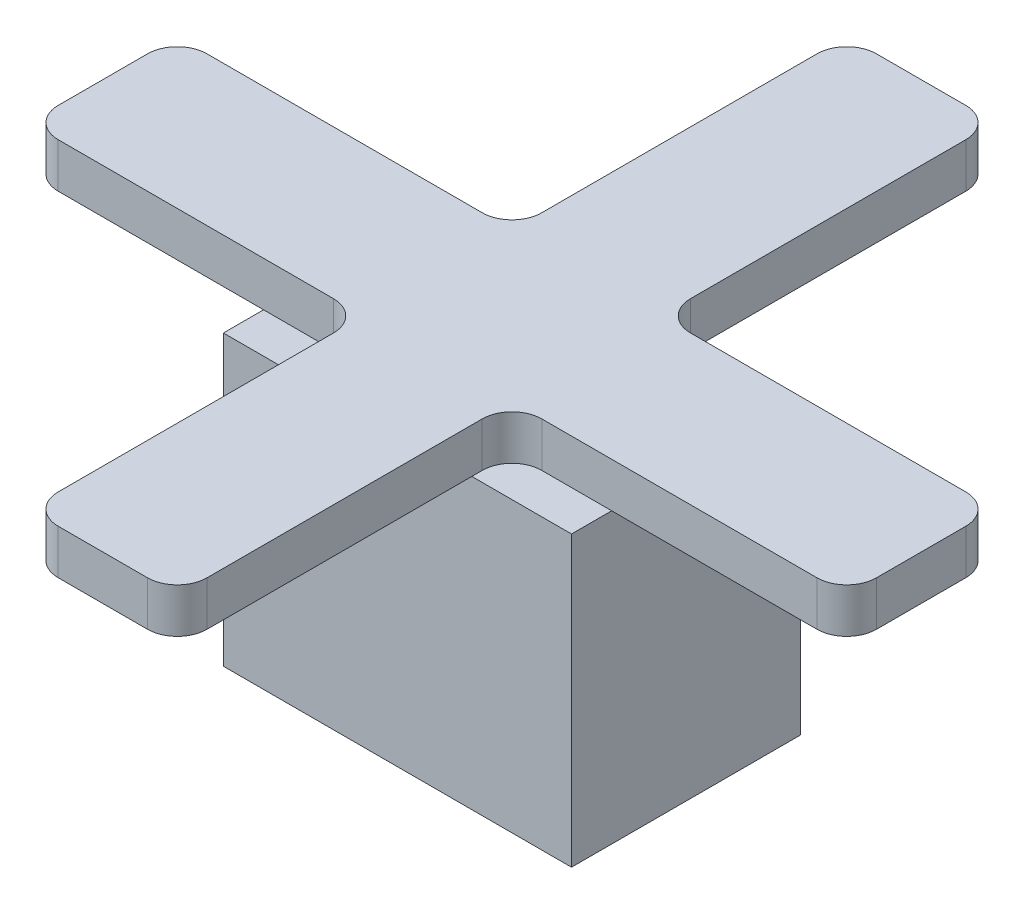
SolidWorks part; units mm, degrees
ref_plane "前视基准面" through (0, 0, 0) normal (0, 0, 1) x (1, 0, 0)
ref_plane "上视基准面" through (0, 0, 0) normal (0, 1, 0) x (1, 0, 0)
ref_plane "右视基准面" through (0, 0, 0) normal (1, 0, 0) x (0, 0, -1)
sketch "草图1" plane through (0, 0, 0) normal (0, 1, 0) x (1, 0, 0)
  line L0 (7, 5) -> (25.5, 5)
  line L1 (-25.5, 5) -> (-7, 5)
  line L2 (-27.5, 3) -> (-27.5, -3)
  line L3 (-25.5, -5) -> (-7, -5)
  line L4 (27.5, 3) -> (27.5, -3)
  line L7 (-3, 27.5) -> (3, 27.5)
  line L8 (-5, 25.5) -> (-5, 7)
  line L9 (-3, -27.5) -> (3, -27.5)
  line L10 (5, 25.5) -> (5, 7)
  line L16 (7, -5) -> (25.5, -5)
  line L17 (-5, -7) -> (-5, -25.5)
  line L18 (5, -7) -> (5, -25.5)
  arc A0 (3, -27.5) -> (5, -25.5) centre (3, -25.5) ccw
  arc A1 (-5, -25.5) -> (-3, -27.5) centre (-3, -25.5) ccw
  arc A2 (3, 27.5) -> (5, 25.5) centre (3, 25.5) cw
  arc A3 (-3, 27.5) -> (-5, 25.5) centre (-3, 25.5) ccw
  arc A4 (25.5, 5) -> (27.5, 3) centre (25.5, 3) cw
  arc A5 (-25.5, 5) -> (-27.5, 3) centre (-25.5, 3) ccw
  arc A6 (-27.5, -3) -> (-25.5, -5) centre (-25.5, -3) ccw
  arc A7 (-7, -5) -> (-5, -7) centre (-7, -7) cw
  arc A8 (5, -7) -> (7, -5) centre (7, -7) cw
  arc A9 (5, 7) -> (7, 5) centre (7, 7) ccw
  arc A10 (-5, 7) -> (-7, 5) centre (-7, 7) cw
  arc A11 (25.5, -5) -> (27.5, -3) centre (25.5, -3) ccw
  point P0 (0, 0)
  point P6 (0, 0)
  point P11 (0, 27.5)
  point P20 (5, 27.5)
  point P25 (-5, 27.5)
  point P28 (27.5, 5)
  point P31 (-27.5, 5)
  point P36 (-5, -5)
  point P45 (27.5, -5)
  dimension "D5" = 2
  dimension "D6" = 2
  dimension "D1" = 55
  dimension "D2" = 10
  dimension "D3" = 55
  dimension "D4" = 10
extrude "凸台-拉伸1" add sketch "草图1" along normal blind 3
sketch "草图2" plane through (0, 0, 0) normal (0, -1, 0) x (1, 0, 0)
  line L1 (-10.2, 6.2) -> (10.2, 6.2)
  line L2 (-10.2, 6.2) -> (-10.2, -6.2)
  line L3 (-10.2, -6.2) -> (10.2, -6.2)
  line L4 (10.2, 6.2) -> (10.2, -6.2)
  line L5 (-10.2, 6.2) -> (10.2, -6.2) construction
  line L6 (-10.2, -6.2) -> (10.2, 6.2) construction
  line L7 (-11.7, 7.7) -> (11.7, 7.7)
  line L8 (-11.7, 7.7) -> (-11.7, -7.7)
  line L9 (-11.7, -7.7) -> (11.7, -7.7)
  line L10 (11.7, 7.7) -> (11.7, -7.7)
  line L11 (-11.7, 7.7) -> (11.7, -7.7) construction
  line L12 (-11.7, -7.7) -> (11.7, 7.7) construction
  point P0 (0, 0)
  point P6 (0, 0)
  line M8 (-5, 25.5) -> (-5, 7)
  arc M9 (-5, 7) -> (-7, 5) centre (-7, 7) cw
  line M10 (-7, 5) -> (-25.5, 5)
  line M14 (-25.5, -5) -> (-7, -5)
  arc M15 (-7, -5) -> (-5, -7) centre (-7, -7) cw
  line M16 (-5, -7) -> (-5, -25.5)
  line M20 (5, -25.5) -> (5, -7)
  arc M21 (5, -7) -> (7, -5) centre (7, -7) cw
  line M22 (7, -5) -> (25.5, -5)
  line M26 (25.5, 5) -> (7, 5)
  arc M27 (7, 5) -> (5, 7) centre (7, 7) cw
  line M28 (5, 7) -> (5, 25.5)
  dimension "D1" = 12.4
  dimension "D2" = 20.4
  dimension "D3" = 23.4
  dimension "D4" = 15.4
extrude "凸台-拉伸2" add sketch "草图2" along normal blind 3 contours L8 L2 M10 M14 | L7 L8 L2 L1 M10 M9 M8 | L7 L1 M8 M9 M27 M28 | L10 L7 L1 L4 M28 M27 M26 | L10 L4 M26 M22 | L10 L4 L3 L9 M22 M21 M20 | L9 L3 M16 M20 M21 M15 | L8 L9 L3 L2 M16 M15 M14
sketch "草图4" plane through (0, -3, 0) normal (0, -1, 0) x (1, 0, 0)
  line L1 (-11.7, 7.7) -> (11.7, 7.7)
  line L2 (-11.7, 7.7) -> (-11.7, -7.7)
  line L3 (-11.7, -7.7) -> (11.7, -7.7)
  line L4 (11.7, 7.7) -> (11.7, -7.7)
  line L5 (-11.7, 7.7) -> (11.7, -7.7) construction
  line L6 (-11.7, -7.7) -> (11.7, 7.7) construction
  line L7 (-10.2, 6.2) -> (10.2, 6.2)
  line L8 (-10.2, 6.2) -> (-10.2, -6.2)
  line L9 (-10.2, -6.2) -> (10.2, -6.2)
  line L10 (10.2, 6.2) -> (10.2, -6.2)
  line L11 (-10.2, 6.2) -> (10.2, -6.2) construction
  line L12 (-10.2, -6.2) -> (10.2, 6.2) construction
  point P0 (0, 0)
  point P7 (0, 0)
  dimension "D1" = 20.4
  dimension "D2" = 12.4
extrude "凸台-拉伸4" add sketch "草图4" along normal blind 16.4
